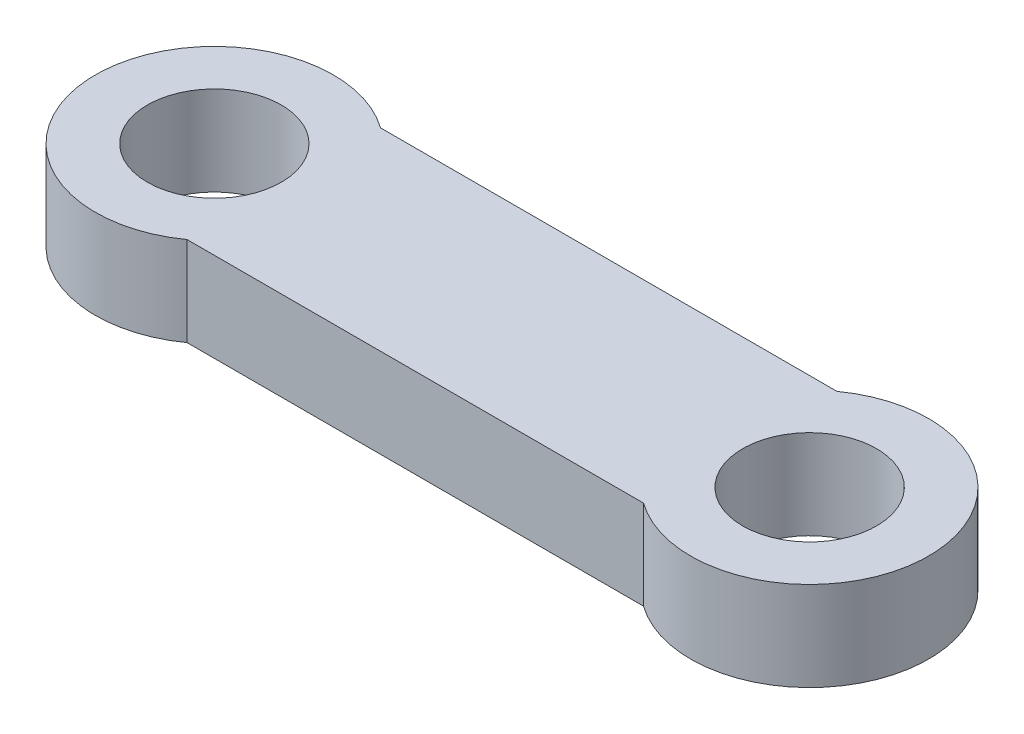
SolidWorks part; units mm, degrees
material "6061 合金"
ref_plane "Front Plane" through (0, 0, 0) normal (0, 0, 1) x (1, 0, 0)
ref_plane "Top Plane" through (0, 0, 0) normal (0, 1, 0) x (1, 0, 0)
ref_plane "Right Plane" through (0, 0, 0) normal (1, 0, 0) x (0, 0, -1)
other "Configuration Table"
sketch "草图1" plane through (0, 0, 0) normal (0, 1, 0) x (1, 0, 0)
  line L0 (-15.3363, 6.5) -> (15.3363, 6.5)
  line L1 (-20, 6.5) -> (20, 6.5) construction
  line L2 (-20, 6.5) -> (-20, -6.5) construction
  line L3 (-20, -6.5) -> (20, -6.5) construction
  line L4 (20, 6.5) -> (20, -6.5) construction
  line L5 (-20, 6.5) -> (20, -6.5) construction
  line L6 (-20, -6.5) -> (20, 6.5) construction
  line L7 (15.3363, -6.5) -> (-15.3363, -6.5)
  arc A0 (-15.3363, -6.5) -> (-15.3363, 6.5) centre (-20, 0) cw
  arc A1 (15.3363, -6.5) -> (15.3363, 6.5) centre (20, 0) ccw
  circle A2 centre (-20, 0) radius 4.5
  circle A3 centre (20, 0) radius 4.5
  point P0 (0, 0)
  dimension "D2" = 8
  dimension "D3" = 8
  dimension "D5" = 9
  dimension "D6" = 9
  dimension "D1" = 40
  dimension "D4" = 13
extrude "凸台-拉伸1" add sketch "草图1" along normal blind 6
